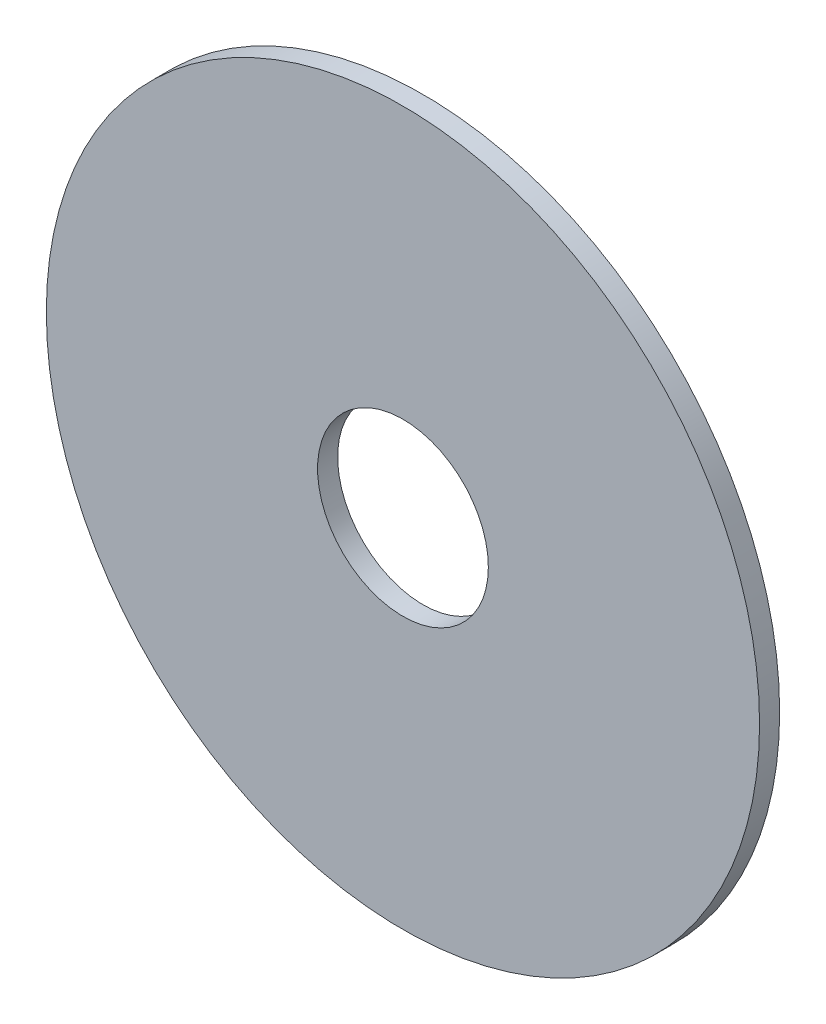
SolidWorks part; units mm, degrees
ref_plane "Alzado" through (0, 0, 0) normal (0, 0, 1) x (1, 0, 0)
ref_plane "Planta" through (0, 0, 0) normal (0, 1, 0) x (1, 0, 0)
ref_plane "Vista lateral" through (0, 0, 0) normal (1, 0, 0) x (0, 0, -1)
sketch "Croquis2" plane through (0, 0, 0) normal (0, 0, 1) x (1, 0, 0)
sketch_block_instance "v-1"
sketch_block "Bloque1"
sketch "Croquis4" plane through (0, 0, 0) normal (0, 0, 1) x (1, 0, 0)
  line L0 (0, 57.5) -> (0, 177.5) construction
  line L1 (28.75, 49.7965) -> (88.75, 153.7195) construction
  line L2 (49.7965, 28.75) -> (153.7195, 88.75) construction
  line L3 (57.5, 0) -> (177.5, 0) construction
  line L4 (49.7965, -28.75) -> (153.7195, -88.75) construction
  line L5 (28.75, -49.7965) -> (88.75, -153.7195) construction
  line L6 (0, -57.5) -> (0, -177.5) construction
  line L7 (-28.75, -49.7965) -> (-88.75, -153.7195) construction
  line L8 (-49.7965, -28.75) -> (-153.7195, -88.75) construction
  line L9 (-57.5, 0) -> (-177.5, 0) construction
  line L10 (-49.7965, 28.75) -> (-153.7195, 88.75) construction
  line L11 (-28.75, 49.7965) -> (-88.75, 153.7195) construction
  circle A0 centre (0, 0) radius 177.5
  circle A1 centre (0, 0) radius 216.259
  circle A2 centre (0, 0) radius 57.5
  circle A3 centre (0, 0) radius 42.5
  arc A4 (57.5, 0) -> (177.5, 0) centre (117.5, -153.7043) cw
  arc A5 (49.7965, -28.75) -> (153.7195, -88.75) centre (24.9059, -191.8618) cw
  arc A6 (28.75, -49.7965) -> (88.75, -153.7195) centre (-74.3618, -178.6101) cw
  arc A7 (0, -57.5) -> (0, -177.5) centre (-153.7043, -117.5) cw
  arc A8 (-28.75, -49.7965) -> (-88.75, -153.7195) centre (-191.8618, -24.9059) cw
  arc A9 (-49.7965, -28.75) -> (-153.7195, -88.75) centre (-178.6101, 74.3618) cw
  arc A10 (-57.5, 0) -> (-177.5, 0) centre (-117.5, 153.7043) cw
  arc A11 (-49.7965, 28.75) -> (-153.7195, 88.75) centre (-24.9059, 191.8618) cw
  arc A12 (-28.75, 49.7965) -> (-88.75, 153.7195) centre (74.3618, 178.6101) cw
  arc A13 (0, 57.5) -> (0, 177.5) centre (153.7043, 117.5) cw
  arc A14 (28.75, 49.7965) -> (88.75, 153.7195) centre (191.8618, 24.9059) cw
  arc A15 (49.7965, 28.75) -> (153.7195, 88.75) centre (178.6101, -74.3618) cw
  point P9 (0, 0)
  point P32 (0, 0)
  point P33 (0, 0)
  point P67 (0, 0)
  dimension "D1" = 355
  dimension "D2" = 432.518
  dimension "D3" = 115
  dimension "D4" = 85
  dimension "D6" = 12
  dimension "D7" = 122.8156
  dimension "D5" = 12
sketch "Croquis6" plane through (0, 0, 0) normal (0, 0, 1) x (1, 0, 0)
  circle A0 centre (0, 0) radius 177.5
  circle A1 centre (0, 0) radius 42.5
extrude "Saliente-Extruir1" add sketch "Croquis6" along normal blind 10
